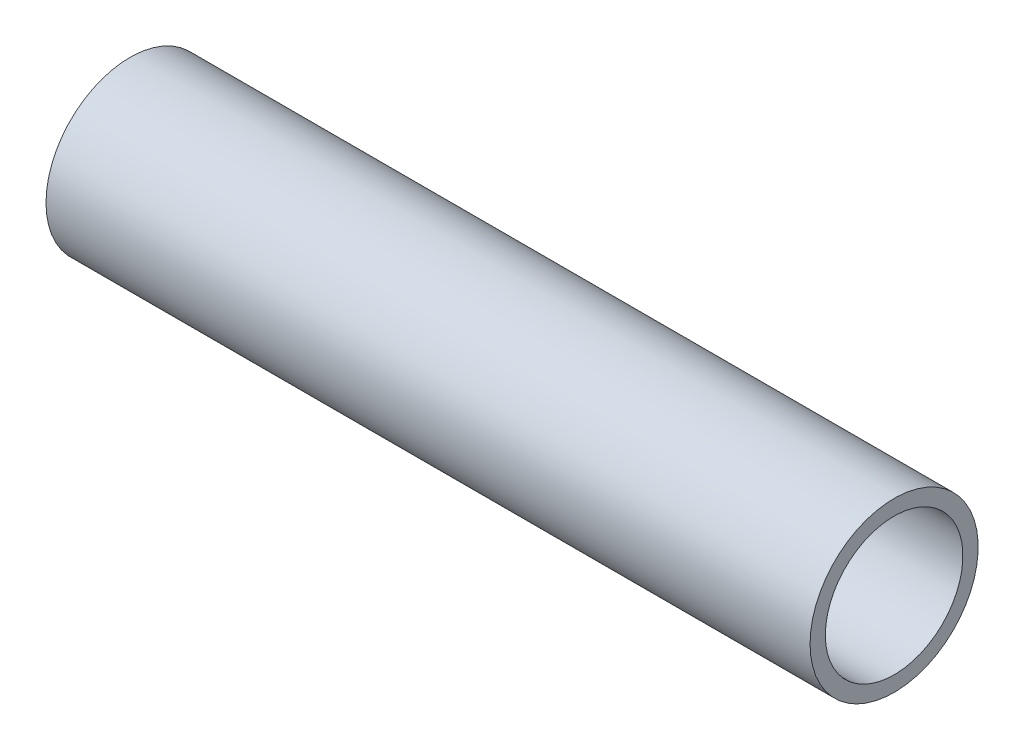
SolidWorks part; units mm, degrees
ref_plane "Front Plane" through (0, 0, 0) normal (0, 0, 1) x (1, 0, 0)
ref_plane "Top Plane" through (0, 0, 0) normal (0, 1, 0) x (1, 0, 0)
ref_plane "Right Plane" through (0, 0, 0) normal (1, 0, 0) x (0, 0, -1)
sketch "Sketch1" plane through (0, 0, 0) normal (0, 1, 0) x (1, 0, 0)
  line L1 (0, 0) -> (-250, 0)
  line L2 (0, 0) -> (0, 5)
  line L3 (0, 5) -> (-250, 5)
  line L4 (-250, 0) -> (-250, 5)
  line L9 (-13.7374, 0) -> (0, 0)
  line L10 (0, -5) -> (0, 0)
  line L11 (-250, -22.5) -> (-66.7987, -22.5)
  dimension "D1" = 250
  dimension "D2" = 5
  dimension "D6" = 22.5
revolve "Revolve1" add sketch "Sketch1" angle 360 about L11
